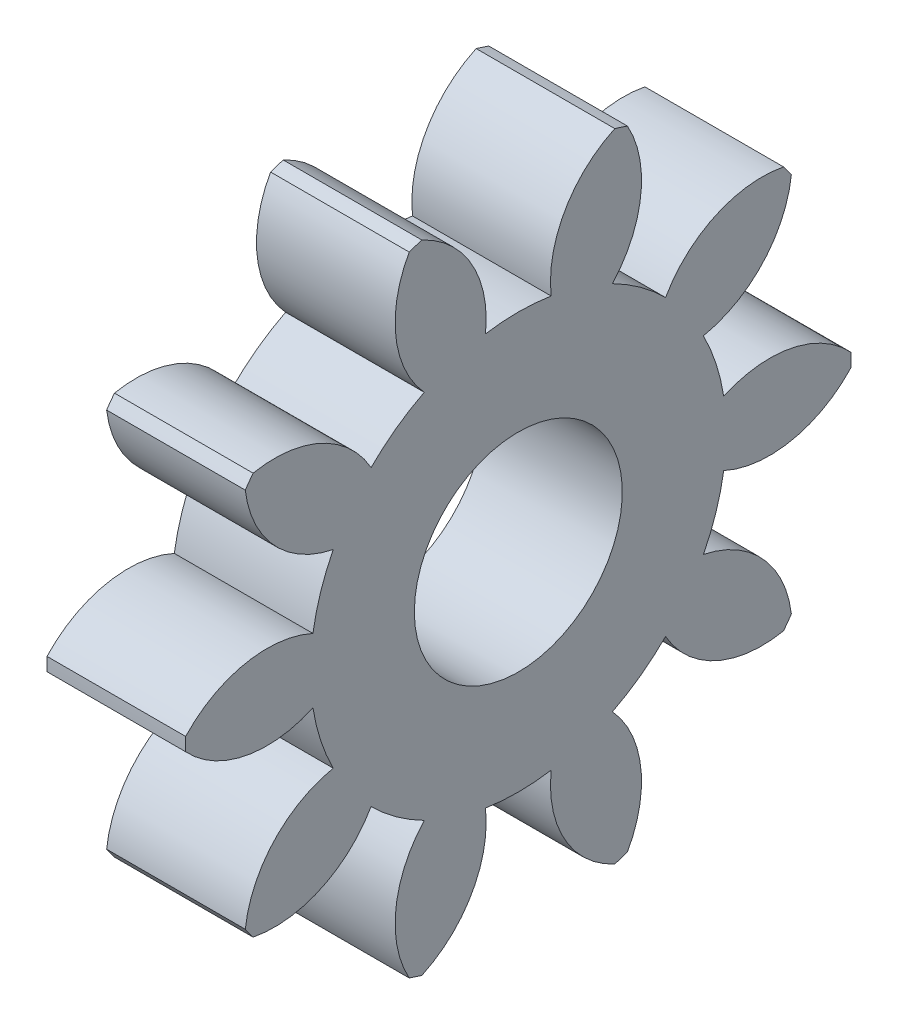
SolidWorks part; units mm, degrees
ref_plane "Plane1" through (0, 0, 0) normal (0, 0, 1) x (1, 0, 0)
ref_plane "Plane2" through (0, 0, 0) normal (0, 1, 0) x (1, 0, 0)
ref_plane "Plane3" through (0, 0, 0) normal (1, 0, 0) x (0, 0, -1)
sketch "HoldingSke" plane through (0, 0, 0) normal (0, 1, 0) x (1, 0, 0)
  line L0 (0, 0) -> (1.231, -0.2171)
  line L1 (-15, 0) -> (100, 0) construction
  line L2 (0, 0) -> (-2.1039, 2.3779)
  line L3 (0, 0) -> (-11.863, 4.5341)
  line L4 (0, 0) -> (8.5048, 1.4996)
  line L5 (0, 0) -> (-46.8476, -17.4728)
  line L6 (0, 0) -> (-1.6579, -1.1186)
  line L7 (-2.1039, 2.3779) -> (8.6586, 51.2059)
  line L8 (-76.2, 54.61) -> (-75.7, 54.61)
  line L9 (-71.009, 38.7566) -> (-53.1078, 45.2721)
  line L10 (-76.2, 71.12) -> (104.1128, 71.12)
  line L11 (0, 0) -> (-2, 0)
  line L12 (-76.2, 101.6) -> (-76.17, 101.6)
  line L13 (24.9733, 27.94) -> (52.9518, 28.4284)
  line L14 (24.9733, 27.94) -> (24.9743, 27.94)
  line L15 (24.9733, 27.94) -> (100.4006, 29.5858)
  line L16 (-63.627, -0.8) -> (-12.827, -0.8)
  circle A0 centre (0, 0) radius 1.5
  circle A1 centre (0, 0) radius 2.999
  circle A2 centre (0, 0) radius 37.5
  circle A3 centre (0, 0) radius 1.5
  dimension "MHD" = 5.998
  dimension "Hub_dia" = 75
  dimension "Bore" = 3
  dimension "MBD" = 3
  dimension "Num_teeth" = 10
  dimension "Pitch" = 1.25
  dimension "Overall_len" = 50
  dimension "Show_teeth" = 10
  dimension "Thickness" = 2
  dimension "OAL" = 50.0001
  dimension "T_dim" = 0.5
  dimension "Ap" = 20
  dimension "H" = 19.05
  dimension "Pitch_radius" = 180.3128
  dimension "Width" = 2
  dimension "Backlash" = 0.03
  dimension "Addendum_fac" = 1
  dimension "Dedendum_fac" = 1.25
  dimension "Clearance_fac" = 0.25
  dimension "Dedendum_add" = 0.001
  dimension "Module" = 0.8
sketch "BasProSke" plane through (0, 0, 0) normal (0, 1, 0) x (1, 0, 0)
  line L0 (-10, 0) -> (60, 0) construction
  line L1 (0, 0) -> (0, 4.8)
  line L2 (0, 0) -> (2, 0)
  line L3 (2, 0) -> (2, 4.8)
  line L4 (2, 4.8) -> (0, 4.8)
  dimension "Thickness" = 2
  dimension "Diameter" = 9.6
revolve "Base-Revolve" add sketch "BasProSke" angle 360 about L0
sketch "TooCutSke" plane through (0, 0, 0) normal (1, 0, 0) x (0, 0, -1)
  line L1 (0, 0) -> (0, 107) construction
  line L2 (0, 0) -> (-0.6781, 3.9421) construction
  line L3 (0, 0) -> (-2.4466, 7.5299) construction
  line L4 (-0.6781, 3.9421) -> (-1.2233, 3.765) construction
  arc A0 (0.4737, 2.9613) -> (-0.4737, 2.9613) centre (0, 0) ccw
  arc A1 (1.4269, 4.6096) -> (-1.4269, 4.6096) centre (0, 0) ccw
  circle A2 centre (0, 0) radius 4 construction
  circle A3 centre (0, 0) radius 3.7588 construction
  arc A4 (-0.4737, 2.9613) -> (-1.4269, 4.6096) centre (-2.0635, 3.1417) ccw
  arc A5 (1.4269, 4.6096) -> (0.4737, 2.9613) centre (2.0635, 3.1417) ccw
  dimension "Root_dia" = 5.998
  dimension "Overcut_dia" = 9.6508
  dimension "Pitch_dia" = 8
  dimension "Base_dia" = 7.5175
  dimension "Flank_rad" = 1.6
  dimension "Half_ang" = 18
  dimension "Half_CT" = 0.5732
extrude "ToothCut" cut sketch "TooCutSke" along normal through all
fillet "Breaks" [suppressed] radius 0.016
fillet "RootFillets" [suppressed] radius 0.201
pattern_circular "TeethCuts" count 10 every 36 about axis through (-10, 0, 0) along (1, 0, 0) of "ToothCut", "RootFillets", "Breaks"
sketch "HubNeaOneSke" plane through (0, 0, 0) normal (-1, 0, 0) x (0, 0, 1)
  circle A0 centre (0, 0) radius 2.999
  dimension "Diameter" = 5.998
extrude "HubNearOne" [suppressed] add sketch "HubNeaOneSke" along normal blind 48.0001
sketch "HubNeaBotSke" plane through (0, 0, 0) normal (-1, 0, 0) x (0, 0, 1)
  circle A0 centre (0, 0) radius 2.999
  dimension "Diameter" = 5.998
extrude "HubNearBoth" [suppressed] add sketch "HubNeaBotSke" along normal blind 24
ref_plane "FarPln" through (2, 0, 0) normal (1, 0, 0) x (0, 0, -1)
sketch "HubFarSke" plane through (2, 0, 0) normal (1, 0, 0) x (0, 0, -1)
  circle A0 centre (0, 0) radius 2.999
  dimension "Diameter" = 5.998
extrude "HubFar" [suppressed] add sketch "HubFarSke" along normal blind 24
sketch "BorSke" plane through (0, 0, 0) normal (1, 0, 0) x (0, 0, -1)
  circle A0 centre (0, 0) radius 1.5
  dimension "Diameter" = 3
extrude "Bore" cut sketch "BorSke" along normal mid plane 100.0001
sketch "KeySke" plane through (0, 0, 0) normal (1, 0, 0) x (0, 0, -1)
  line L0 (-0.6, 0) -> (-0.6, 2)
  line L1 (-0.6, 2) -> (0.6, 2)
  line L2 (0.6, 2) -> (0.6, 0)
  line L3 (0, 0) -> (0, 34) construction
  line L4 (-0.6, 0) -> (0.6, 0)
  dimension "Offset" = 2
  dimension "Width" = 1.2
extrude "Keyway" [suppressed] cut sketch "KeySke" along normal mid plane 100.0001
pattern_circular "Keyway2" [suppressed] count 2 every 90 about axis through (-10, 0, 0) along (1, 0, 0)
equation "' \"Module@HoldingSke\" = 6.35"
equation "' \"Num_teeth@HoldingSke\" = 12"
equation "' \"Ap@HoldingSke\" =  20"
equation "' \"Ap@HoldingSke\" = 20"
equation "' \"Width@HoldingSke\" = 0.5 * 25.4"
equation "' \"Hub_dia@HoldingSke\"= 1 * 25.4"
equation "' \"Hub_dia@HoldingSke\" = 1 * 25.4"
equation "' \"Overall_len@HoldingSke\" = 1.0 * 25.4"
equation "' \"Bore@HoldingSke\" = 0.75 * 25.4"
equation "' \"T_dim@HoldingSke\" = 0.1 * 25.4"
equation "' \"Width@KeySke\" = 0.25 * 25.4"
equation "' \"Show_teeth@HoldingSke\" = 13"
equation "' \"Backlash@HoldingSke\" = 0.009 * 25.4"
equation "' \"Addendum_fac@HoldingSke\" = 1.0"
equation "' \"Dedendum_fac@HoldingSke\" = 1.25"
equation "' \"Dedendum_add@HoldingSke\" = 0.00005 * 25.4"
equation "' \"Clearance_fac@HoldingSke\" = 0.25"
equation "\"Pitch@HoldingSke\" = 1 / \"Module@HoldingSke\""
equation "\"Overcut_dia@TooCutSke\" = (\"Num_teeth@HoldingSke\" + 2 * \"Addendum_fac@HoldingSke\") / \"Pitch@HoldingSke\" + 0.002 * 25.4"
equation "\"Pitch_dia@TooCutSke\" = \"Num_teeth@HoldingSke\" / \"Pitch@HoldingSke\""
equation "\"Base_dia@TooCutSke\" = \"Num_teeth@HoldingSke\" / \"Pitch@HoldingSke\" * cos((\"Ap@HoldingSke\"  * 3.14159265 / 180))"
equation "\"Root_dia@TooCutSke\" = (\"Num_teeth@HoldingSke\" + 2) / \"Pitch@HoldingSke\" - 2 * (\"Addendum_fac@HoldingSke\" + \"Dedendum_fac@HoldingSke\") / \"Pitch@HoldingSke\" - \"Dedendum_add@HoldingSke\" * 2"
equation "\"Half_ang@TooCutSke\" = 180 / \"Num_teeth@HoldingSke\""
equation "\"Half_CT@TooCutSke\" = \"Num_teeth@HoldingSke\" / \"Pitch@HoldingSke\" * sin((3.14159265 / 2 / \"Num_teeth@HoldingSke\")) / 2 - 7 * \"Backlash@HoldingSke\" / 4"
equation "\"Flank_rad@TooCutSke\" = \"Num_teeth@HoldingSke\" / \"Pitch@HoldingSke\" / 5"
equation "\"Radius@RootFillets\" = \"Clearance_fac@HoldingSke\" / \"Pitch@HoldingSke\" + \"Dedendum_add@HoldingSke\""
equation "\"Break_rad@Breaks\" = 0.02 / \"Pitch@HoldingSke\""
equation "\"Thickness@HoldingSke\" = \"Width@HoldingSke\""
equation "\"OAL@HoldingSke\" = \"Thickness@HoldingSke\""
equation "\"MHD@HoldingSke\" = (\"Num_teeth@HoldingSke\" + 2) / \"Pitch@HoldingSke\" - 2 * (\"Addendum_fac@HoldingSke\" + \"Dedendum_fac@HoldingSke\")  / \"Pitch@HoldingSke\" - \"Dedendum_add@HoldingSke\" * 2"
equation "\"MBD@HoldingSke\" = (\"Num_teeth@HoldingSke\" + 2) / \"Pitch@HoldingSke\" - 2 * (\"Addendum_fac@HoldingSke\" + \"Dedendum_fac@HoldingSke\")  / \"Pitch@HoldingSke\" - \"Dedendum_add@HoldingSke\" * 2 - 0.002 * 25.4"
equation "\"MHD@HoldingSke\" = ((sgn( \"MHD@HoldingSke\" - \"Hub_dia@HoldingSke\" )-1)*( \"MHD@HoldingSke\" - \"Hub_dia@HoldingSke\" ))/-2+ \"Hub_dia@HoldingSke\""
equation "\"MBD@HoldingSke\" = ((sgn( \"MBD@HoldingSke\" - \"Bore@HoldingSke\" )-1)*( \"MBD@HoldingSke\" - \"Bore@HoldingSke\" ))/-2+ \"Bore@HoldingSke\""
equation "\"OAL@HoldingSke\" = ((sgn( \"OAL@HoldingSke\" - \"Overall_len@HoldingSke\" )+1)*( \"OAL@HoldingSke\" - \"Overall_len@HoldingSke\" ))/2 + \"Overall_len@HoldingSke\" + 0.000002 * 25.4"
equation "\"Num_teeth@TeethCuts\" = int( \"Show_teeth@HoldingSke\" ) + 1"
equation "\"Num_teeth@TeethCuts\" = ((sgn( \"Num_teeth@TeethCuts\" - \"Num_teeth@HoldingSke\" )-1)*( \"Num_teeth@TeethCuts\" - \"Num_teeth@HoldingSke\" ))/-2+ \"Num_teeth@HoldingSke\""
equation "\"Num_teeth@TeethCuts\" = ((sgn( \"Num_teeth@TeethCuts\" - 2.0)+1)*( \"Num_teeth@TeethCuts\" - 2.0))/2 +2.0"
equation "\"Angle@TeethCuts\" = 360.0 / \"Num_teeth@HoldingSke\""
equation "\"Diameter@BasProSke\" = (\"Num_teeth@HoldingSke\" + 2 * \"Addendum_fac@HoldingSke\") / \"Pitch@HoldingSke\""
equation "\"Thickness@BasProSke\"  = \"Thickness@HoldingSke\""
equation "' \"Fillet_rad@BasProSke\" =  \"Thickness@HoldingSke\" * 0.05"
equation "' \"Fillet_rad@BasProSke\" = \"Thickness@HoldingSke\" * 0.05"
equation "\"MHD@HoldingSke\" = ((sgn( \"MHD@HoldingSke\" - \"Root_dia@TooCutSke\" )-1)*( \"MHD@HoldingSke\" - \"Root_dia@TooCutSke\" ))/-2+ \"Root_dia@TooCutSke\""
equation "\"Diameter@HubNeaOneSke\" = \"MHD@HoldingSke\""
equation "\"Length@HubNearOne\" = \"OAL@HoldingSke\" - \"Thickness@BasProSke\""
equation "\"Diameter@HubNeaBotSke\" = \"MHD@HoldingSke\""
equation "\"Length@HubNearBoth\" = ( \"OAL@HoldingSke\" - \"Thickness@BasProSke\" ) / 2.0"
equation "\"Thickness@FarPln\" = \"Thickness@BasProSke\""
equation "\"Diameter@HubFarSke\" = \"MHD@HoldingSke\""
equation "\"Length@HubFar\" = ( \"OAL@HoldingSke\" - \"Thickness@BasProSke\" ) / 2.0"
equation "\"Diameter@BorSke\" = \"MBD@HoldingSke\""
equation "\"D1@Bore\" = \"OAL@HoldingSke\" * 2.0"
equation "\"D1@Keyway\" = \"OAL@HoldingSke\" * 2.0"
equation "\"Offset@KeySke\" = \"T_dim@HoldingSke\" + \"MBD@HoldingSke\" / 2.0"
